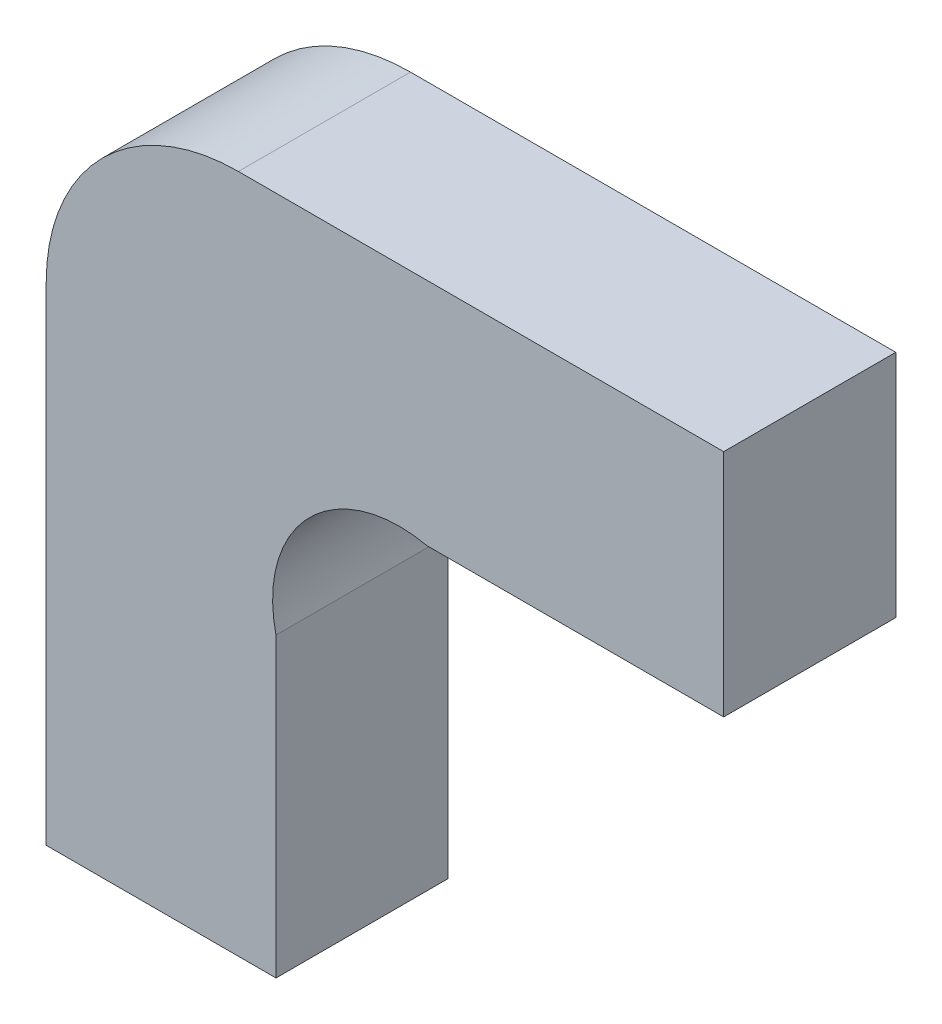
SolidWorks part; units mm, degrees
ref_plane "Front Plane" through (0, 0, 0) normal (0, 0, 1) x (1, 0, 0)
ref_plane "Top Plane" through (0, 0, 0) normal (0, 1, 0) x (1, 0, 0)
ref_plane "Right Plane" through (0, 0, 0) normal (1, 0, 0) x (0, 0, -1)
sketch "Sketch1" plane through (0, 0, 0) normal (0, 0, 1) x (1, 0, 0)
  line L0 (-97.1952, 54.414) -> (-97.1952, -70.0657)
  line L1 (-97.1952, -70.0657) -> (-38.5212, -70.0657)
  line L2 (-38.5212, -70.0657) -> (-38.5212, 5.7737)
  line L3 (-48.1233, 103.4859) -> (75.7923, 103.4859)
  line L4 (75.7923, 103.4859) -> (75.7923, 44.8119)
  line L7 (0, 44.8119) -> (75.7923, 44.8119)
  arc A0 (-48.1233, 103.4859) -> (-97.1952, 54.414) centre (-48.1233, 54.414) ccw
  arc A2 (-38.5212, 5.7737) -> (0, 44.8119) centre (-7.0217, 13.2159) cw
extrude "Boss-Extrude1" add sketch "Sketch1" along normal blind 43.942
